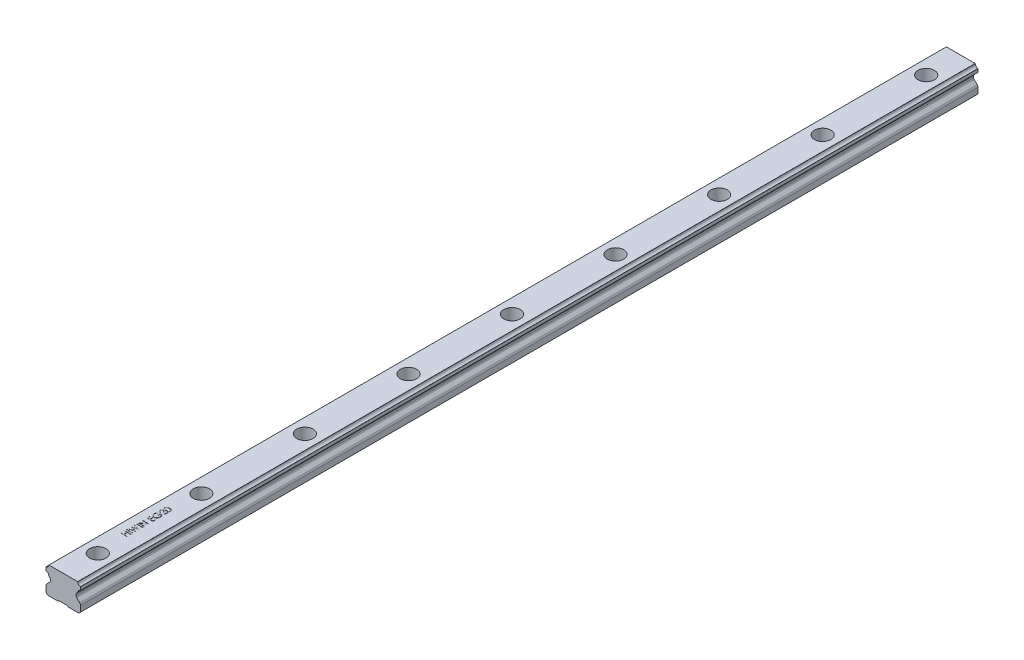
SolidWorks part; units mm, degrees
material "镀铬不锈钢"
ref_plane "前视基准面" through (0, 0, 0) normal (0, 0, 1) x (1, 0, 0)
ref_plane "上视基准面" through (0, 0, 0) normal (0, 1, 0) x (1, 0, 0)
ref_plane "右视基准面" through (0, 0, 0) normal (1, 0, 0) x (0, 0, -1)
sketch "草图1" plane through (0, 0, 0) normal (0, 0, 1) x (1, 0, 0)
  line L0 (8.3896, 15.4446) -> (8.3342, 15.5)
  line L1 (8.3342, 15.5) -> (-8.3342, 15.5)
  line L2 (-8.3342, 15.5) -> (-8.3896, 15.4446)
  line L3 (-10, 13.647) -> (-10, 11.953)
  line L4 (-8.3896, 10.1554) -> (-7.7929, 9.5587)
  line L5 (-7.5, 8.8516) -> (-7.5, 7.9143)
  line L6 (-7.7929, 7.2072) -> (-9.5607, 5.4394)
  line L7 (-10, 4.3787) -> (-10, 1)
  line L8 (-10, 1) -> (-9, 0)
  line L9 (-9, 0) -> (-3, 0)
  line L10 (-3, 0) -> (-2.5, 0.5)
  line L11 (-2.5, 0.5) -> (2.5, 0.5)
  line L12 (2.5, 0.5) -> (3, 0)
  line L13 (3, 0) -> (9, 0)
  line L14 (9, 0) -> (10, 1)
  line L15 (10, 1) -> (10, 4.3787)
  line L16 (9.5607, 5.4394) -> (7.7929, 7.2072)
  line L17 (7.5, 7.9143) -> (7.5, 8.8516)
  line L18 (7.7929, 9.5587) -> (8.3896, 10.1554)
  line L19 (10, 11.953) -> (10, 13.647)
  line L20 (-3, 0) -> (3, 0) construction
  line L21 (0, 0) -> (0, 15.5) construction
  arc A0 (10, 13.647) -> (9.9603, 13.7961) centre (9.7, 13.647) ccw
  arc A1 (8.3896, 15.4446) -> (9.9603, 13.7961) centre (10.1371, 15.5371) ccw
  arc A2 (-9.9603, 13.7961) -> (-8.3896, 15.4446) centre (-10.1371, 15.5371) ccw
  arc A3 (-9.9603, 13.7961) -> (-10, 13.647) centre (-9.7, 13.647) ccw
  arc A4 (-10, 11.953) -> (-9.9603, 11.8039) centre (-9.7, 11.953) ccw
  arc A5 (-8.3896, 10.1554) -> (-9.9603, 11.8039) centre (-10.1371, 10.0629) ccw
  arc A6 (-7.5, 8.8516) -> (-7.7929, 9.5587) centre (-8.5, 8.8516) ccw
  arc A7 (-7.7929, 7.2072) -> (-7.5, 7.9143) centre (-8.5, 7.9143) ccw
  arc A8 (-9.5607, 5.4394) -> (-10, 4.3787) centre (-8.5, 4.3787) ccw
  arc A9 (10, 4.3787) -> (9.5607, 5.4394) centre (8.5, 4.3787) ccw
  arc A10 (7.5, 7.9143) -> (7.7929, 7.2072) centre (8.5, 7.9143) ccw
  arc A11 (7.7929, 9.5587) -> (7.5, 8.8516) centre (8.5, 8.8516) ccw
  arc A12 (9.9603, 11.8039) -> (8.3896, 10.1554) centre (10.1371, 10.0629) ccw
  arc A13 (9.9603, 11.8039) -> (10, 11.953) centre (9.7, 11.953) ccw
extrude "凸台-拉伸1" add sketch "草图1" against normal blind 520
hole_wizard "M5 六角凹头螺钉的柱形沉头孔1" positions "草图3" profile "草图2" counterbore size "M5" standard "ISO" end condition through all
sketch "草图3" plane through (0.803, 15.5, -26.9155) normal (0, 1, 0) x (-1, 0, 0)
  point P0 (0.803, 6.9155)
  dimension "D1" = 20
sketch "草图2" plane through (0, 15.5, -20) normal (1, 0, 0) x (0, 0, 1)
  line L0 (0, 0) -> (0, 15.5)
  line L1 (0, 15.5) -> (3, 15.5)
  line L3 (3, 15.5) -> (3, 8.5)
  line L4 (3, 8.5) -> (4.75, 8.5)
  line L5 (4.75, 8.5) -> (4.75, 0)
  line L7 (4.75, 0) -> (0, 0)
  line L11 (0, -6.35) -> (0, 107.95) construction
  dimension "通孔孔直径" = 6
  dimension "通孔孔深度" = 15.5
  dimension "柱形沉头孔直径" = 9.5
  dimension "柱形沉头孔深度" = 8.5
pattern_linear "阵列(线性)1" count 9 spacing 60 along (0, 0, -1) of "M5 六角凹头螺钉的柱形沉头孔1"
sketch "草图6" plane through (0, 15.5, 0) normal (0, 1, 0) x (1, 0, 0)
  line L0 (0, 20) -> (0, 80) construction
  text T0 "HIWIN EG20"
extrude "切除-拉伸1" cut sketch "草图6" against normal blind 0.1
equation "\"D1@凸台-拉伸1\" = 2 * \"D1@草图3\" + \"D3@阵列(线性)1\" *  ( \"D1@阵列(线性)1\"  - 1) "
